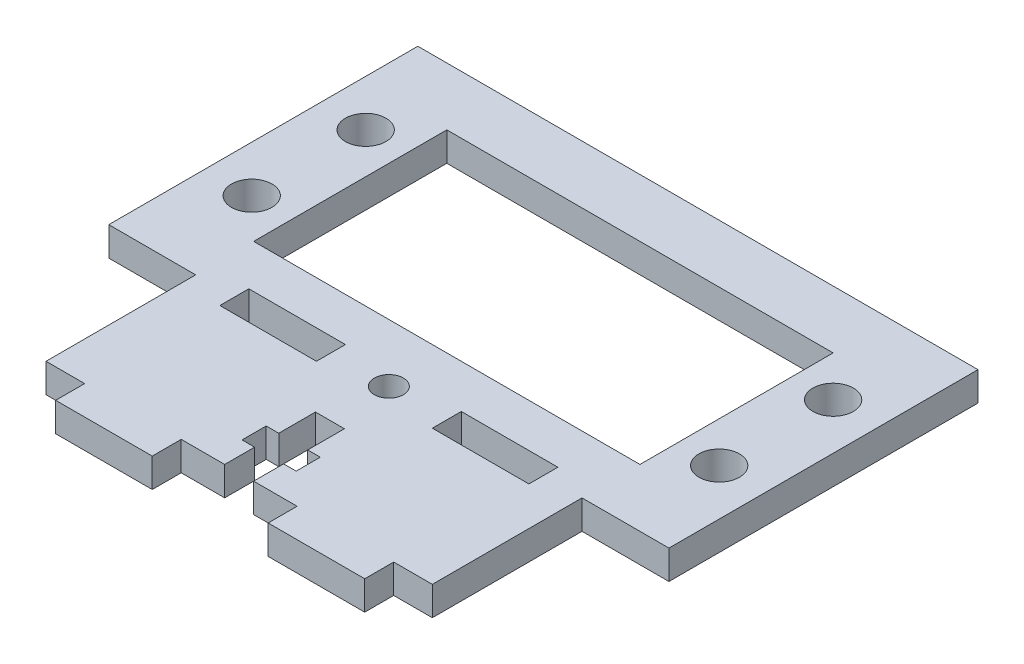
SolidWorks part; units mm, degrees
ref_plane "Front Plane" through (0, 0, 0) normal (0, 0, 1) x (1, 0, 0)
ref_plane "Top Plane" through (0, 0, 0) normal (0, 1, 0) x (1, 0, 0)
ref_plane "Right Plane" through (0, 0, 0) normal (1, 0, 0) x (0, 0, -1)
sketch "Sketch2" plane through (0, 0, 0) normal (0, 1, 0) x (1, 0, 0)
  line L0 (0, 15.5) -> (9, 15.5)
  line L1 (0, 0) -> (-4, 0)
  line L2 (0, 0) -> (0, 15.5)
  line L4 (-40, 0) -> (-40, 15.5)
  line L5 (9, 15.5) -> (9, 47.5)
  line L6 (0, 41.5) -> (-40, 41.5)
  line L7 (-49, 47.5) -> (-49, 15.5)
  line L8 (-49, 15.5) -> (-40, 15.5)
  line L9 (-20, 41.5) -> (-20, 9.4) construction
  line L11 (0, 21.5) -> (-40, 21.5)
  line L12 (-40, 21.5) -> (-40, 41.5)
  line L13 (-40, 41.5) -> (0, 41.5)
  line L14 (0, 41.5) -> (0, 21.5)
  line L15 (9, 47.5) -> (-49, 47.5)
  line L16 (-4, 0) -> (-4, -3)
  line L17 (-4, -3) -> (-14, -3)
  line L18 (-14, -3) -> (-14, 0)
  line L19 (-14, 0) -> (-18.5, 0)
  line L20 (-26, -3) -> (-26, 0)
  line L21 (-36, -3) -> (-26, -3)
  line L22 (-36, 0) -> (-36, -3)
  line L23 (-36, 0) -> (-40, 0)
  line L24 (-26, 17) -> (-26, 14)
  line L25 (-18.5, 0) -> (-18.5, 3.1)
  line L26 (-18.5, 3.1) -> (-17.2, 3.1)
  line L27 (-17.2, 3.1) -> (-17.2, 5.6)
  line L28 (-17.2, 5.6) -> (-18.5, 5.6)
  line L29 (-18.5, 5.6) -> (-18.5, 9.4)
  line L30 (-18.5, 9.4) -> (-21.5, 9.4)
  line L31 (-21.5, 9.4) -> (-21.5, 5.6)
  line L32 (-21.5, 5.6) -> (-22.8, 5.6)
  line L33 (-22.8, 5.6) -> (-22.8, 3.1)
  line L34 (-22.8, 3.1) -> (-21.5, 3.1)
  line L35 (-21.5, 3.1) -> (-21.5, 0)
  line L36 (-21.5, 0) -> (-26, 0)
  line L37 (-4, 14) -> (-4, 17)
  line L38 (-4, 17) -> (-14, 17)
  line L39 (-14, 17) -> (-14, 14)
  line L40 (-14, 14) -> (-4, 14)
  line L41 (-36, 14) -> (-36, 17)
  line L42 (-36, 17) -> (-26, 17)
  line L43 (-26, 14) -> (-36, 14)
  line L44 (-14, 15.5) -> (-26, 15.5) construction
  circle A0 centre (4.2, 25.5) radius 2.1
  circle A1 centre (4.2, 37.3) radius 2.1
  circle A2 centre (-44.2, 37.3) radius 2.1
  circle A3 centre (-44.2, 25.5) radius 2.1
  circle A4 centre (-20, 15.5) radius 1.5
  point P23 (-4, 0)
  point P57 (0, 0)
  dimension "D6" = 4
  dimension "D7" = 4.2
  dimension "D8" = 11.8
  dimension "D21" = 3
  dimension "D1" = 15.5
  dimension "D2" = 40
  dimension "D3" = 9
  dimension "D4" = 4.2
  dimension "D5" = 32
  dimension "D9" = 20
  dimension "D10" = 6
  dimension "D11" = 4
  dimension "D12" = 10
  dimension "D13" = 3
  dimension "D14" = 1.3
  dimension "D15" = 3.1
  dimension "D16" = 2.5
  dimension "D17" = 3.8
  dimension "D18" = 3
  dimension "D19" = 4.5
  dimension "D20" = 1.5
extrude "Boss-Extrude1" add sketch "Sketch2" along normal blind 3
